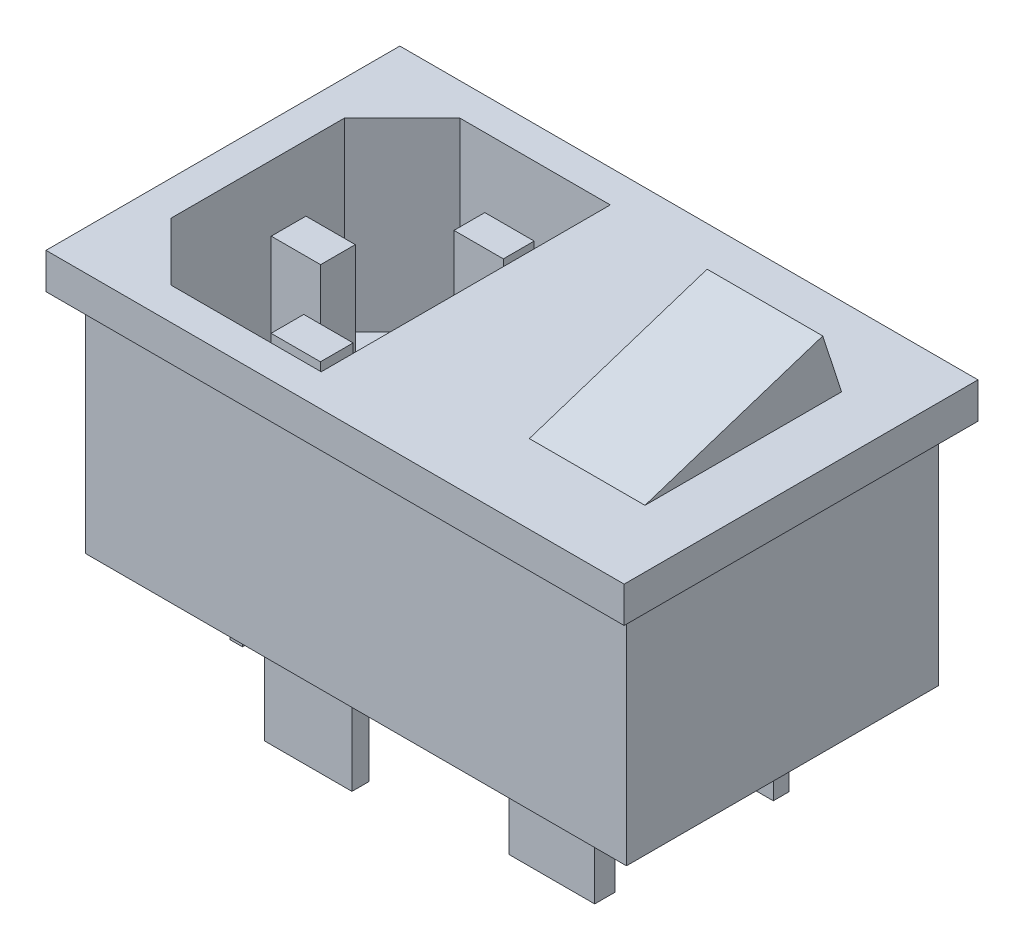
SolidWorks part; units mm, degrees
ref_plane "前视基准面" through (0, 0, 0) normal (0, 0, 1) x (1, 0, 0)
ref_plane "上视基准面" through (0, 0, 0) normal (0, 1, 0) x (1, 0, 0)
ref_plane "右视基准面" through (0, 0, 0) normal (1, 0, 0) x (0, 0, -1)
sketch "草图1" plane through (0, 0, 0) normal (0, 1, 0) x (1, 0, 0)
  line L1 (-25, -15.3) -> (25, -15.3)
  line L2 (-25, -15.3) -> (-25, 15.3)
  line L3 (-25, 15.3) -> (25, 15.3)
  line L4 (25, -15.3) -> (25, 15.3)
  line L5 (-25, -15.3) -> (25, 15.3) construction
  line L6 (-25, 15.3) -> (25, -15.3) construction
  point P0 (0, 0)
  dimension "D1" = 30.6
  dimension "D2" = 50
extrude "凸台-拉伸1" add sketch "草图1" along normal blind 3.1
sketch "草图2" plane through (0, 0, 0) normal (0, -1, 0) x (1, 0, 0)
  line L1 (-23.4, -13.5) -> (23.4, -13.5)
  line L2 (-23.4, -13.5) -> (-23.4, 13.5)
  line L3 (-23.4, 13.5) -> (23.4, 13.5)
  line L4 (23.4, -13.5) -> (23.4, 13.5)
  line L5 (-23.4, -13.5) -> (23.4, 13.5) construction
  line L6 (-23.4, 13.5) -> (23.4, -13.5) construction
  point P0 (0, 0)
  dimension "D1" = 46.8
  dimension "D2" = 27
extrude "凸台-拉伸2" add sketch "草图2" along normal blind 19.7
sketch "草图3" plane through (0, 3.1, 0) normal (0, 1, 0) x (1, 0, 0)
  line L1 (-17, 12.5) -> (-4, 12.5)
  line L2 (-22, 7.5) -> (-22, -7.5)
  line L3 (-17, -12.5) -> (-4, -12.5)
  line L4 (-4, 12.5) -> (-4, -12.5)
  line L5 (-25, 15.3) -> (-25, -15.3) construction
  line L7 (-17, 12.5) -> (-22, 7.5)
  line L8 (-4, 0) -> (-22, 0) construction
  line L9 (-17, -12.5) -> (-22, -7.5)
  dimension "D1" = 25
  dimension "D2" = 3
  dimension "D3" = 18
  dimension "D4" = 5
  dimension "D5" = 5
extrude "切除-拉伸1" cut sketch "草图3" against normal blind 16
sketch "草图4" plane through (0, -12.9, 0) normal (0, 1, 0) x (1, 0, 0)
  line L1 (-19.3205, 1.5003) -> (-15.0529, 1.5003)
  line L2 (-19.3205, 1.5003) -> (-19.3205, -1.5003)
  line L3 (-19.3205, -1.5003) -> (-15.0529, -1.5003)
  line L4 (-15.0529, 1.5003) -> (-15.0529, -1.5003)
  line L5 (-19.3205, 1.5003) -> (-15.0529, -1.5003) construction
  line L6 (-19.3205, -1.5003) -> (-15.0529, 1.5003) construction
  line L7 (-11.8522, 9.5021) -> (-7.5846, 9.5021)
  line L8 (-11.8522, 9.5021) -> (-11.8522, 6.8349)
  line L9 (-11.8522, 6.8349) -> (-7.5846, 6.8349)
  line L10 (-7.5846, 9.5021) -> (-7.5846, 6.8349)
  line L11 (-11.8522, 9.5021) -> (-7.5846, 6.8349) construction
  line L12 (-11.8522, 6.8349) -> (-7.5846, 9.5021) construction
  line L13 (-12.0522, -5.9549) -> (-7.7846, -5.9549)
  line L14 (-12.0522, -5.9549) -> (-12.0522, -8.7818)
  line L15 (-12.0522, -8.7818) -> (-7.7846, -8.7818)
  line L16 (-7.7846, -5.9549) -> (-7.7846, -8.7818)
  line L17 (-12.0522, -5.9549) -> (-7.7846, -8.7818) construction
  line L18 (-12.0522, -8.7818) -> (-7.7846, -5.9549) construction
  point P0 (-17.1867, 0)
  point P5 (-9.7184, 8.1685)
  point P10 (-9.9184, -7.3683)
extrude "凸台-拉伸3" add sketch "草图4" along normal blind 13
sketch "草图5" plane through (25, 0, 0) normal (1, 0, 0) x (0, 0, -1)
  line L0 (-8.5, 3.1) -> (6.8739, 8.1)
  line L1 (-15.3, 3.1) -> (15.3, 3.1) construction
  line L2 (6.8739, 8.1) -> (8.5, 3.1)
  line L3 (8.5, 3.1) -> (-8.5, 3.1)
  line L4 (-13.5, -19.7) -> (-13.5, 0) construction
  line L5 (13.5, -19.7) -> (13.5, 0) construction
  dimension "D1" = 5
  dimension "D2" = 5
  dimension "D3" = 5
extrude "凸台-拉伸4" add sketch "草图5" against normal blind 10 from offset 5 offset against normal yes
sketch "草图6" plane through (0, -19.7, 0) normal (0, -1, 0) x (1, 0, 0)
  line L1 (-19.6885, 4.7046) -> (-18.6007, 4.7046)
  line L2 (-19.6885, 4.7046) -> (-19.6885, -2.7466)
  line L3 (-19.6885, -2.7466) -> (-18.6007, -2.7466)
  line L4 (-18.6007, 4.7046) -> (-18.6007, -2.7466)
  line L5 (-10.6057, 10.796) -> (-3.0457, 10.796)
  line L6 (-10.6057, 10.796) -> (-10.6057, 9.3276)
  line L7 (-10.6057, 9.3276) -> (-3.0457, 9.3276)
  line L8 (-3.0457, 10.796) -> (-3.0457, 9.3276)
  line L9 (-10.6057, -6.7169) -> (-2.665, -6.7169)
  line L10 (-10.6057, -6.7169) -> (-10.6057, -8.0766)
  line L11 (-10.6057, -8.0766) -> (-2.665, -8.0766)
  line L12 (-2.665, -6.7169) -> (-2.665, -8.0766)
  line L13 (8.4845, 8.7293) -> (15.8813, 8.7293)
  line L14 (8.4845, 8.7293) -> (8.4845, 6.9889)
  line L15 (8.4845, 6.9889) -> (15.8813, 6.9889)
  line L16 (15.8813, 8.7293) -> (15.8813, 6.9889)
  line L17 (8.4845, -6.7169) -> (15.8813, -6.7169)
  line L18 (8.4845, -6.7169) -> (8.4845, -8.0766)
  line L19 (8.4845, -8.0766) -> (15.8813, -8.0766)
  line L20 (15.8813, -6.7169) -> (15.8813, -8.0766)
extrude "凸台-拉伸5" add sketch "草图6" along normal blind 9
